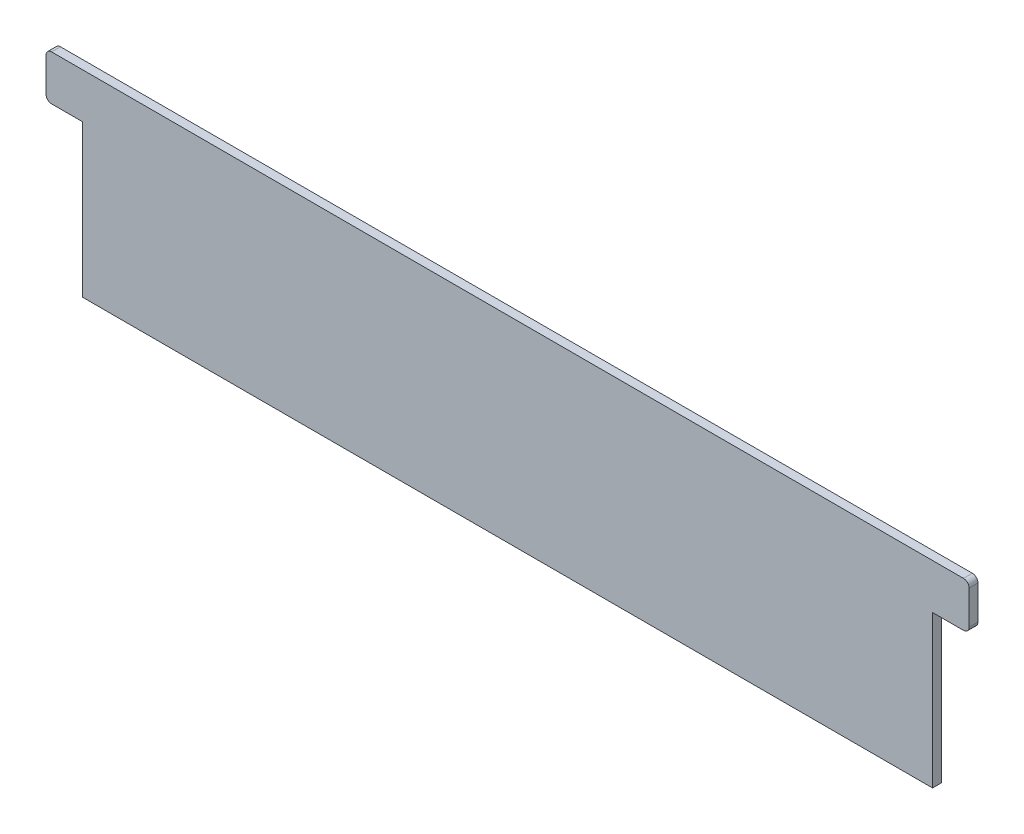
SolidWorks part; units mm, degrees
material "Oak"
ref_plane "Front Plane" through (0, 0, 0) normal (0, 0, 1) x (1, 0, 0)
ref_plane "Top Plane" through (0, 0, 0) normal (0, 1, 0) x (1, 0, 0)
ref_plane "Right Plane" through (0, 0, 0) normal (1, 0, 0) x (0, 0, -1)
sketch "Sketch1" plane through (0, 0, 0) normal (0, 0, 1) x (1, 0, 0)
  line L0 (-260.35, 68.2625) -> (260.35, 68.2625)
  line L1 (260.35, 68.2625) -> (260.35, 42.8625)
  line L2 (260.35, 42.8625) -> (239.7125, 42.8625)
  line L3 (239.7125, 42.8625) -> (239.7125, -42.8625)
  line L4 (239.7125, -42.8625) -> (-239.7125, -42.8625)
  line L5 (-239.7125, -42.8625) -> (-239.7125, 42.8625)
  line L6 (-239.7125, 42.8625) -> (-260.35, 42.8625)
  line L7 (-260.35, 42.8625) -> (-260.35, 68.2625)
  point P3 (0, 68.2625)
  point P12 (-239.7125, 0)
  dimension "D1" = 25.4
  dimension "D2" = 520.7
  dimension "D3" = 479.425
  dimension "D4" = 85.725
extrude "Boss-Extrude1" add sketch "Sketch1" along normal mid plane 5
fillet "Fillet1" radius 3.175 4 edges at (-260.35, 42.8625, 0) (-260.35, 68.2625, 0) (260.35, 68.2625, 0) (260.35, 42.8625, 0)
